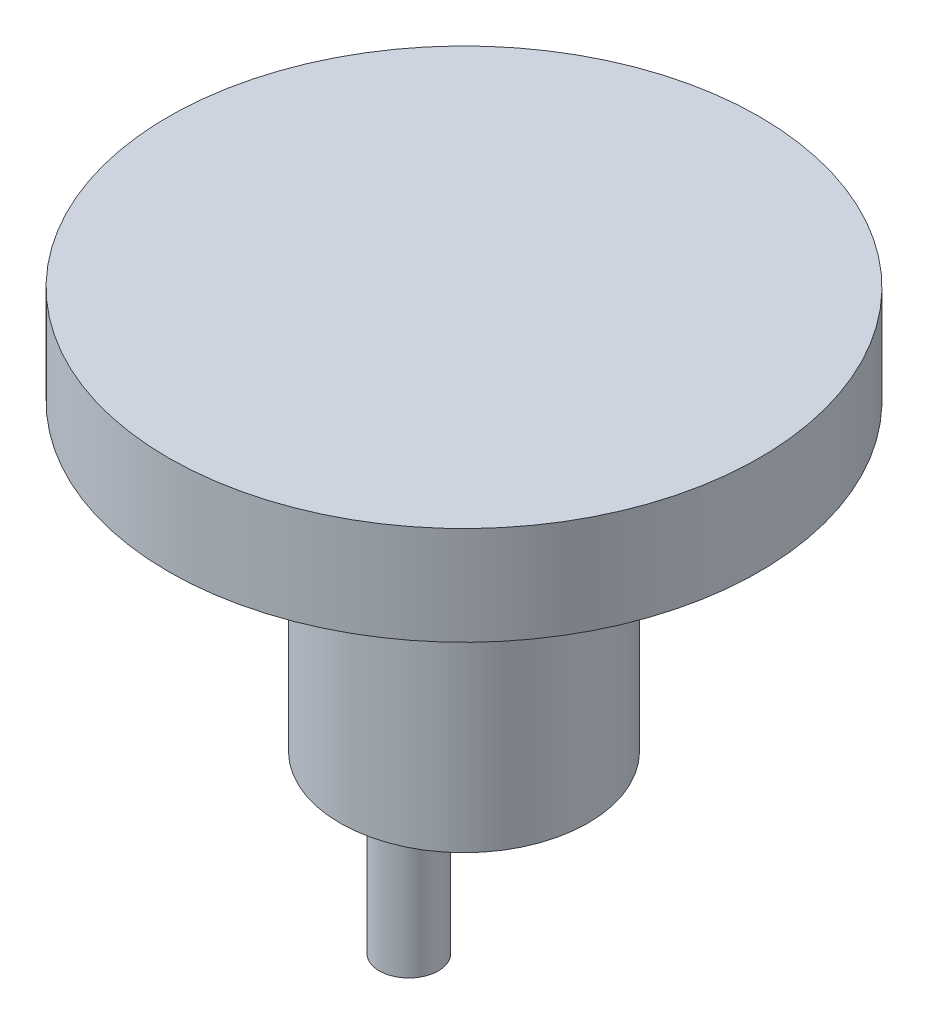
SolidWorks part; units mm, degrees
ref_plane "Front Plane" through (0, 0, 0) normal (0, 0, 1) x (1, 0, 0)
ref_plane "Top Plane" through (0, 0, 0) normal (0, 1, 0) x (1, 0, 0)
ref_plane "Right Plane" through (0, 0, 0) normal (1, 0, 0) x (0, 0, -1)
sketch "Sketch1" plane through (0, 0, 0) normal (0, 1, 0) x (1, 0, 0)
  circle A0 centre (0, 0) radius 12.6
  dimension "D1" = 25.2
extrude "Boss-Extrude1" add sketch "Sketch1" along normal blind 29.3
sketch "Sketch2" plane through (0, 29.3, 0) normal (0, 1, 0) x (1, 0, 0)
  circle A0 centre (0, 0) radius 1.75
  dimension "D1" = 3.5
extrude "Boss-Extrude2" add sketch "Sketch2" along normal blind 11.5
sketch "Sketch3" plane through (0, 40.8, 0) normal (0, 1, 0) x (1, 0, 0)
  circle A0 centre (0, 0) radius 30
  dimension "D1" = 60
extrude "Boss-Extrude3" add sketch "Sketch3" against normal blind 10
sketch "Sketch4" plane through (0, 0, 0) normal (0, -1, 0) x (1, 0, 0)
  circle A2 centre (0, 5.6) radius 3
  dimension "D1" = 5.6
  dimension "D2" = 6
extrude "Boss-Extrude4" add sketch "Sketch4" along normal blind 15
